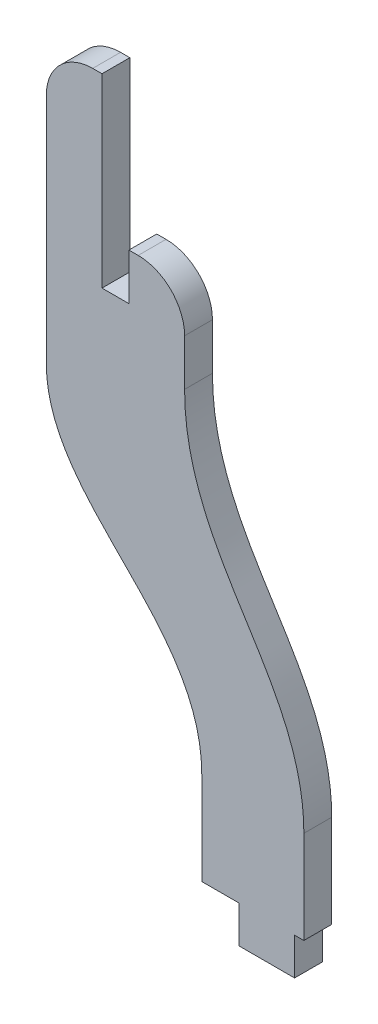
SolidWorks part; units mm, degrees
ref_plane "Front Plane" through (0, 0, 0) normal (0, 0, 1) x (1, 0, 0)
ref_plane "Top Plane" through (0, 0, 0) normal (0, 1, 0) x (1, 0, 0)
ref_plane "Right Plane" through (0, 0, 0) normal (1, 0, 0) x (0, 0, -1)
sketch "Sketch1" plane through (0, 0, 0) normal (0, 0, 1) x (1, 0, 0)
  line L0 (0, 0) -> (-11, 0)
  line L1 (0, 0) -> (0, 10)
  line L2 (18, 50) -> (18, 0) construction
  line L3 (-18.85, 55) -> (-18.85, 50)
  line L4 (-18.85, 50) -> (-21.75, 50)
  line L5 (-11, 50) -> (-11, 0) construction
  line L6 (-21.75, 50) -> (-21.75, 70)
  line L7 (-1, 0) -> (-7, 0)
  line L8 (-1, 0) -> (-1, -4)
  line L9 (-1, -4) -> (-7, -4)
  line L10 (-7, 0) -> (-7, -4)
  line L11 (-21.75, 70) -> (-27.75, 70)
  line L12 (-18.85, 55) -> (-12.85, 55)
  line L13 (-12.85, 55) -> (-12.85, 45)
  line L14 (-27.75, 70) -> (-27.75, 40)
  line L15 (-11, 0) -> (-11, 10)
  spline S0 degree 3 poles (-11, 10) (-11, 23.7563) (-27.75, 27.6116) (-27.75, 40) knots 0 0 0 0 1 1 1 1
  spline S1 degree 3 poles (-12.85, 45) (-12.85, 29.8683) (0, 23.9495) (0, 10) knots 0 0 0 0 1 1 1 1
  point P16 (-21.75, 60)
  dimension "D1" = 4
  dimension "D2" = 6
  dimension "D3" = 1
  dimension "D4" = 4
  dimension "D5" = 50
  dimension "D6" = 10
  dimension "D7" = 29
  dimension "D8" = 2.9
  dimension "D9" = 39.75
  dimension "D10" = 20
  dimension "D11" = 5
  dimension "D12" = 6
  dimension "D13" = 6
  dimension "D14" = 30
  dimension "D15" = 10
  dimension "D16" = 10
extrude "Boss-Extrude1" add sketch "Sketch1" along normal blind 3
fillet "Fillet1" radius 5 2 edges at (-12.85, 55, 1.5) (-27.75, 70, 1.5)
